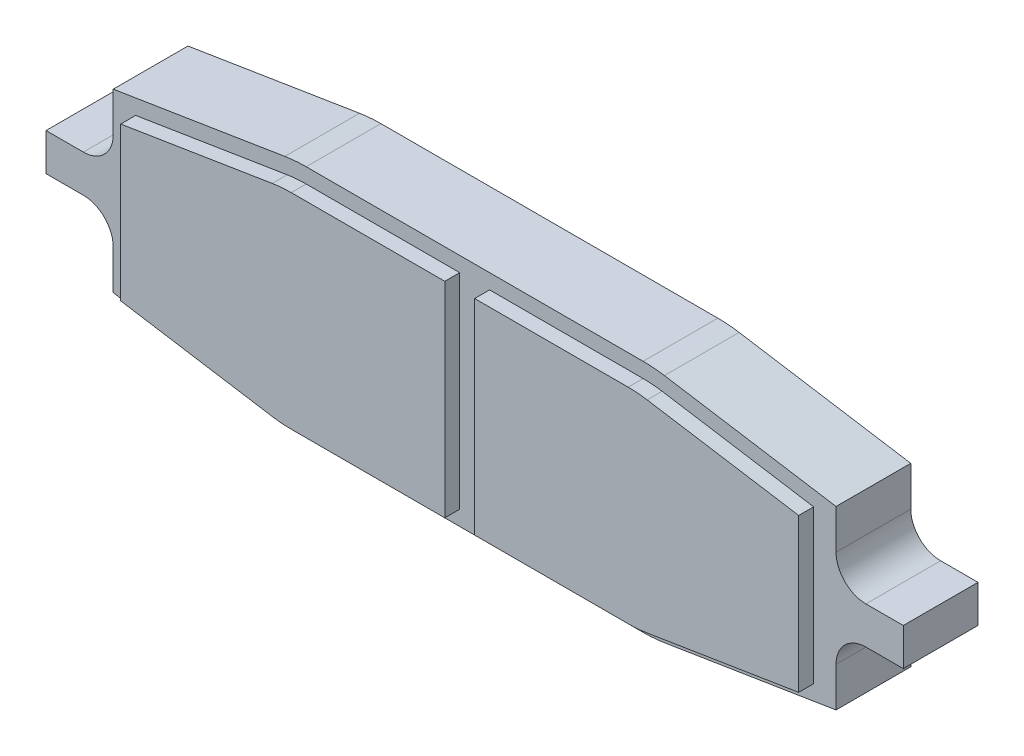
SolidWorks part; units mm, degrees
ref_plane "Front Plane" through (0, 0, 0) normal (0, 0, 1) x (1, 0, 0)
ref_plane "Top Plane" through (0, 0, 0) normal (0, 1, 0) x (1, 0, 0)
ref_plane "Right Plane" through (0, 0, 0) normal (1, 0, 0) x (0, 0, -1)
sketch "Sketch1" plane through (0, 0, 0) normal (0, 0, 1) x (1, 0, 0)
  line L0 (0, 39.6686) -> (0, -39.6686) construction
  line L1 (-50.3702, -14.1004) -> (-50.3702, -7.1004) construction
  line L2 (-50.3702, -9.1004) -> (-50.3702, -16.1004) construction
  line L3 (-52.3702, -7.1004) -> (-57.3702, -7.1004) construction
  line L4 (-52.3702, 1.8996) -> (-57.3702, 1.8996) construction
  line L5 (-59.3702, -5.1004) -> (-59.3702, -0.1004) construction
  line L6 (-50.3702, 3.8996) -> (-50.3702, 9.1952) construction
  line L7 (-50.3702, 17.1114) -> (54.6448, 17.1114) construction
  line L8 (-22.5495, 15.1114) -> (22.5495, 15.1114) construction
  line L9 (-48.6873, 11.1699) -> (-25.7209, 14.8583) construction
  line L10 (48.6873, 11.1699) -> (25.7209, 14.8583) construction
  line L11 (50.3702, 3.8996) -> (50.3702, 9.1952) construction
  line L12 (59.3702, -5.1004) -> (59.3702, -0.1004) construction
  line L13 (52.3702, 1.8996) -> (57.3702, 1.8996) construction
  line L15 (52.3702, -7.1004) -> (57.3702, -7.1004) construction
  line L16 (50.3702, -9.1004) -> (50.3702, -16.1004) construction
  line L17 (-50.3702, 1.8996) -> (-50.3702, 34.3996) construction
  line L18 (-59.3702, -2.6004) -> (59.3702, -2.6004) construction
  line L19 (50.3702, -16.1004) -> (25.7209, -20.0591) construction
  line L20 (-50.3702, -16.1004) -> (-25.7209, -20.0591) construction
  line L21 (-22.5495, -20.3122) -> (22.5495, -20.3122) construction
  line L22 (-48.3702, -9.1004) -> (-48.3702, -14.396)
  line L23 (-48.3702, -14.396) -> (-25.4037, -18.0844)
  line L24 (-22.5495, -18.3122) -> (22.5495, -18.3122)
  line L25 (48.3702, -14.396) -> (25.4037, -18.0844)
  line L26 (48.3702, -9.1004) -> (48.3702, -14.396)
  line L27 (52.3702, -5.1004) -> (57.3702, -5.1004)
  line L28 (57.3702, -5.1004) -> (57.3702, -0.1004)
  line L29 (52.3702, -0.1004) -> (57.3702, -0.1004)
  line L30 (48.3702, 3.8996) -> (48.3702, 9.1952)
  line L31 (48.3702, 9.1952) -> (25.4037, 12.8836)
  line L32 (-22.5495, 13.1114) -> (22.5495, 13.1114)
  line L33 (-48.3702, 9.1952) -> (-25.4037, 12.8836)
  line L34 (-48.3702, 3.8996) -> (-48.3702, 9.1952)
  line L35 (-52.3702, -0.1004) -> (-57.3702, -0.1004)
  line L36 (-57.3702, -5.1004) -> (-57.3702, -0.1004)
  line L37 (-52.3702, -5.1004) -> (-57.3702, -5.1004)
  circle A0 centre (0, -12.6004) radius 32.8 construction
  circle A1 centre (-71.6851, -12.6004) radius 5.115 construction
  arc A2 (25.7209, 14.8583) -> (22.5495, 15.1114) centre (22.5495, -4.8886) ccw construction
  arc A3 (-25.7209, 14.8583) -> (-22.5495, 15.1114) centre (-22.5495, -4.8886) cw construction
  arc A4 (59.3702, -0.1004) -> (57.3702, 1.8996) centre (57.3702, -0.1004) ccw construction
  arc A5 (59.3702, -5.1004) -> (57.3702, -7.1004) centre (57.3702, -5.1004) cw construction
  arc A6 (50.3702, -9.1004) -> (52.3702, -7.1004) centre (52.3702, -9.1004) cw construction
  arc A7 (50.3702, 3.8996) -> (52.3702, 1.8996) centre (52.3702, 3.8996) ccw construction
  arc A8 (48.6873, 11.1699) -> (50.3702, 9.1952) centre (48.3702, 9.1952) cw construction
  arc A9 (-50.3702, 9.1952) -> (-48.6873, 11.1699) centre (-48.3702, 9.1952) cw construction
  arc A10 (-52.3702, -7.1004) -> (-50.3702, -9.1004) centre (-52.3702, -9.1004) cw construction
  arc A11 (-50.3702, 3.8996) -> (-52.3702, 1.8996) centre (-52.3702, 3.8996) cw construction
  arc A12 (-57.3702, 1.8996) -> (-59.3702, -0.1004) centre (-57.3702, -0.1004) ccw construction
  arc A13 (-57.3702, -7.1004) -> (-59.3702, -5.1004) centre (-57.3702, -5.1004) cw construction
  arc A14 (25.7209, -20.0591) -> (22.5495, -20.3122) centre (22.5495, -0.3122) cw construction
  arc A15 (-25.7209, -20.0591) -> (-22.5495, -20.3122) centre (-22.5495, -0.3122) ccw construction
  arc A16 (-25.4037, -18.0844) -> (-22.5495, -18.3122) centre (-22.5495, -0.3122) ccw
  arc A17 (25.4037, -18.0844) -> (22.5495, -18.3122) centre (22.5495, -0.3122) cw
  arc A18 (48.3702, -9.1004) -> (52.3702, -5.1004) centre (52.3702, -9.1004) cw
  arc A21 (48.3702, 3.8996) -> (52.3702, -0.1004) centre (52.3702, 3.8996) ccw
  arc A23 (25.4037, 12.8836) -> (22.5495, 13.1114) centre (22.5495, -4.8886) ccw
  arc A24 (-25.4037, 12.8836) -> (-22.5495, 13.1114) centre (-22.5495, -4.8886) cw
  arc A26 (-48.3702, 3.8996) -> (-52.3702, -0.1004) centre (-52.3702, 3.8996) cw
  arc A29 (-52.3702, -5.1004) -> (-48.3702, -9.1004) centre (-52.3702, -9.1004) cw
  arc A30 (-57.3702, -5.1004) -> (-57.3702, -5.1004) centre (-57.3702, -5.1004) cw construction
  arc A31 (-57.3702, -0.1004) -> (-57.3702, -0.1004) centre (-57.3702, -0.1004) ccw construction
  arc A32 (-48.3702, 9.1952) -> (-48.3702, 9.1952) centre (-48.3702, 9.1952) cw construction
  arc A33 (48.3702, 9.1952) -> (48.3702, 9.1952) centre (48.3702, 9.1952) cw construction
  arc A34 (57.3702, -0.1004) -> (57.3702, -0.1004) centre (57.3702, -0.1004) ccw construction
  arc A35 (57.3702, -5.1004) -> (57.3702, -5.1004) centre (57.3702, -5.1004) cw construction
  point P19 (0, 15.1114)
  point P51 (0, 0)
  point P63 (0, 0)
  dimension "D1" = 65.6
  dimension "D2" = 20
  dimension "D4" = 2
extrude "Boss-Extrude1" add sketch "Sketch1" along normal blind 10 contours L37 A29 L22 L23 A16 L24 A17 L25 L26 A18 L27 L28 L29 A21 L30 L31 A23 L32 A24 L33 L34 A26 L35 L36
sketch "Sketch2" plane through (0, 0, 10) normal (0, 0, 1) x (1, 0, 0)
  line L0 (0, 13.1114) -> (0, -18.3122) construction
  line L1 (-2, 11.1114) -> (-2, -16.3122)
  line L2 (2, 11.1114) -> (2, -16.3122)
  line L3 (-45.3702, 7.6514) -> (-45.3702, -12.8521)
  line L4 (45.3702, 7.6514) -> (45.3702, -12.8521)
  line L6 (2, -18.3122) -> (22.5495, -18.3122)
  line L7 (-25.0866, 10.909) -> (-45.3702, 7.6514)
  line L9 (-45.3702, -12.8521) -> (-25.0866, -16.1097)
  line L10 (-22.5495, -16.3122) -> (-2, -16.3122)
  line L11 (-4, 11.1114) -> (-4, -16.3122) construction
  line L12 (-2, 11.1114) -> (-22.5495, 11.1114)
  line L13 (22.5495, 11.1114) -> (2, 11.1114)
  line L14 (4, 11.1114) -> (4, -16.3122) construction
  line L15 (2, -16.3122) -> (22.5495, -16.3122)
  line L16 (-57.3702, -5.1004) -> (-52.3702, -5.1004)
  line L17 (-48.3702, -9.1004) -> (-48.3702, -14.396)
  line L18 (-48.3702, -14.396) -> (-25.4037, -18.0844)
  line L19 (-22.5495, -18.3122) -> (22.5495, -18.3122)
  line L20 (25.4037, -18.0844) -> (48.3702, -14.396)
  line L21 (48.3702, -14.396) -> (48.3702, -9.1004)
  line L22 (52.3702, -5.1004) -> (57.3702, -5.1004)
  line L23 (57.3702, -5.1004) -> (57.3702, -0.1004)
  line L24 (57.3702, -0.1004) -> (52.3702, -0.1004)
  line L25 (48.3702, 3.8996) -> (48.3702, 9.1952)
  line L26 (48.3702, 9.1952) -> (25.4037, 12.8836)
  line L27 (22.5495, 13.1114) -> (-22.5495, 13.1114)
  line L28 (-25.4037, 12.8836) -> (-48.3702, 9.1952)
  line L29 (-48.3702, 9.1952) -> (-48.3702, 3.8996)
  line L30 (-52.3702, -0.1004) -> (-57.3702, -0.1004)
  line L31 (-57.3702, -0.1004) -> (-57.3702, -5.1004)
  line L32 (-57.3702, -5.1004) -> (-52.3702, -5.1004) construction
  line L33 (-48.3702, -9.1004) -> (-48.3702, -14.396) construction
  line L34 (-45.3702, -14.8778) -> (-25.4037, -18.0844)
  line L35 (-22.5495, -18.3122) -> (-2, -18.3122)
  line L37 (48.3702, -14.396) -> (48.3702, -9.1004) construction
  line L38 (52.3702, -5.1004) -> (57.3702, -5.1004) construction
  line L39 (57.3702, -5.1004) -> (57.3702, -0.1004) construction
  line L40 (57.3702, -0.1004) -> (52.3702, -0.1004) construction
  line L41 (48.3702, 3.8996) -> (48.3702, 9.1952) construction
  line L42 (45.3702, 9.677) -> (25.4037, 12.8836)
  line L43 (22.5495, 13.1114) -> (2, 13.1114)
  line L45 (-48.3702, 9.1952) -> (-48.3702, 3.8996) construction
  line L46 (-52.3702, -0.1004) -> (-57.3702, -0.1004) construction
  line L47 (-57.3702, -0.1004) -> (-57.3702, -5.1004) construction
  line L48 (25.0866, -16.1097) -> (45.3702, -12.8521)
  line L49 (43.3702, 7.9726) -> (43.3702, -13.1733) construction
  line L50 (45.3702, 7.6514) -> (25.0866, 10.909)
  line L51 (-25.0866, 10.909) -> (-43.3702, 7.9726) construction
  line L52 (-43.3702, -13.1733) -> (-25.0866, -16.1097) construction
  line L53 (-45.3702, 9.677) -> (-45.3702, -14.8778) construction
  line L54 (43.3702, 7.9726) -> (25.0866, 10.909) construction
  line L55 (-43.3702, 7.9726) -> (-43.3702, -13.1733) construction
  line L56 (-25.4037, 12.8836) -> (-45.3702, 9.677) construction
  line L57 (-2, 13.1114) -> (-22.5495, 13.1114) construction
  line L58 (25.0866, -16.1097) -> (43.3702, -13.1733) construction
  line L59 (25.4037, -18.0844) -> (45.3702, -14.8778) construction
  line L60 (45.3702, 9.677) -> (45.3702, -14.8778) construction
  line L61 (-4, 11.1114) -> (-22.5495, 11.1114) construction
  line L62 (-22.5495, -16.3122) -> (-4, -16.3122) construction
  line L63 (4, -16.3122) -> (22.5495, -16.3122) construction
  line L64 (22.5495, 11.1114) -> (4, 11.1114) construction
  line L65 (-2, 13.1114) -> (-2, -18.3122) construction
  line L66 (2, 13.1114) -> (2, -18.3122) construction
  arc A0 (-25.0866, -16.1097) -> (-22.5495, -16.3122) centre (-22.5495, -0.3122) ccw
  arc A1 (-22.5495, 11.1114) -> (-25.0866, 10.909) centre (-22.5495, -4.8886) ccw
  arc A2 (22.5495, -16.3122) -> (25.0866, -16.1097) centre (22.5495, -0.3122) ccw
  arc A3 (25.0866, 10.909) -> (22.5495, 11.1114) centre (22.5495, -4.8886) ccw
  arc A8 (-48.3702, -9.1004) -> (-52.3702, -5.1004) centre (-52.3702, -9.1004) ccw
  arc A9 (-25.4037, -18.0844) -> (-22.5495, -18.3122) centre (-22.5495, -0.3122) ccw
  arc A10 (22.5495, -18.3122) -> (25.4037, -18.0844) centre (22.5495, -0.3122) ccw
  arc A11 (52.3702, -5.1004) -> (48.3702, -9.1004) centre (52.3702, -9.1004) ccw
  arc A12 (48.3702, 3.8996) -> (52.3702, -0.1004) centre (52.3702, 3.8996) ccw
  arc A13 (25.4037, 12.8836) -> (22.5495, 13.1114) centre (22.5495, -4.8886) ccw
  arc A14 (-22.5495, 13.1114) -> (-25.4037, 12.8836) centre (-22.5495, -4.8886) ccw
  arc A15 (-52.3702, -0.1004) -> (-48.3702, 3.8996) centre (-52.3702, 3.8996) ccw
  arc A16 (-48.3702, -9.1004) -> (-52.3702, -5.1004) centre (-52.3702, -9.1004) ccw construction
  arc A17 (-25.4037, -18.0844) -> (-22.5495, -18.3122) centre (-22.5495, -0.3122) ccw
  arc A18 (22.5495, -18.3122) -> (25.4037, -18.0844) centre (22.5495, -0.3122) ccw
  arc A19 (52.3702, -5.1004) -> (48.3702, -9.1004) centre (52.3702, -9.1004) ccw construction
  arc A20 (48.3702, 3.8996) -> (52.3702, -0.1004) centre (52.3702, 3.8996) ccw construction
  arc A21 (25.4037, 12.8836) -> (22.5495, 13.1114) centre (22.5495, -4.8886) ccw
  arc A23 (-52.3702, -0.1004) -> (-48.3702, 3.8996) centre (-52.3702, 3.8996) ccw construction
  arc A24 (-22.5495, 13.1114) -> (-25.4037, 12.8836) centre (-22.5495, -4.8886) ccw construction
  dimension "D4" = 2
  dimension "3" = 3
  dimension "D1" = 0
  dimension "D2" = 2
  dimension "D3" = 2
extrude "Boss-Extrude2" add sketch "Sketch2" along normal blind 2 contours L50 A3 L13 L14 L15 A2 L48 L4 | L12 A1 L7 L3 L9 A0 L10 L11
